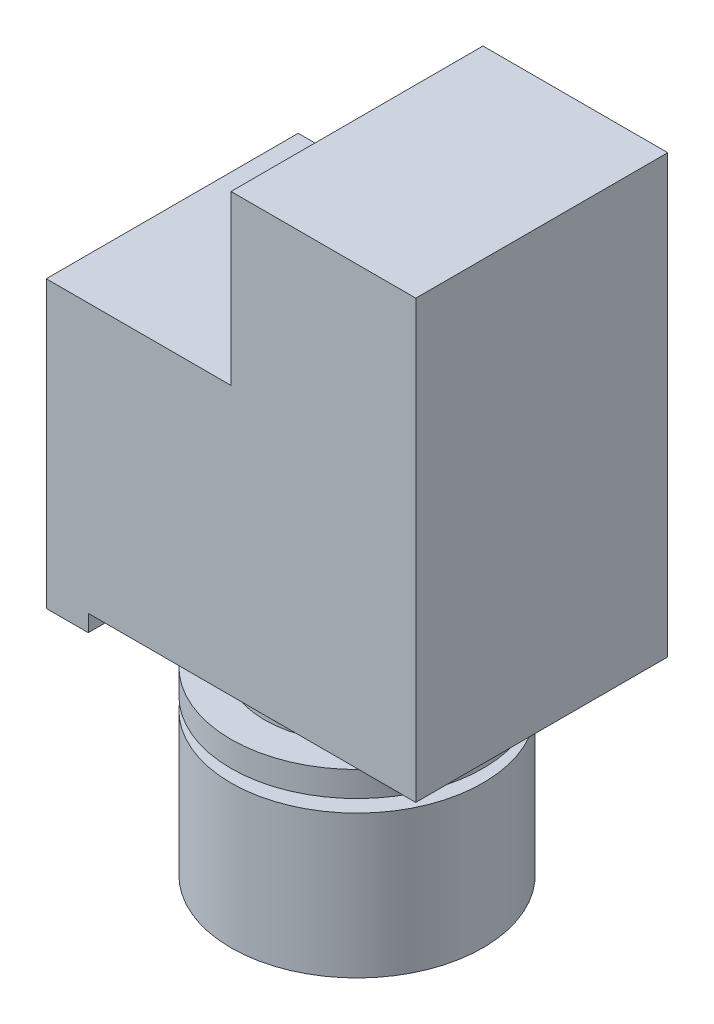
SolidWorks part; units mm, degrees
ref_plane "前基準面" through (0, 0, 0) normal (0, 0, 1) x (1, 0, 0)
ref_plane "上基準面" through (0, 0, 0) normal (0, 1, 0) x (1, 0, 0)
ref_plane "右基準面" through (0, 0, 0) normal (1, 0, 0) x (0, 0, -1)
sketch "草圖1" plane through (0, 0, 0) normal (0, 1, 0) x (1, 0, 0)
  circle A0 centre (0, 0) radius 15
  dimension "D1" = 30
extrude "伸長1" add sketch "草圖1" along normal blind 17
sketch "草圖2" plane through (0, 17, 0) normal (0, 1, 0) x (1, 0, 0)
  circle A0 centre (0, 0) radius 11
  dimension "D1" = 22
extrude "伸長2" add sketch "草圖2" along normal blind 1.5
sketch "草圖3" plane through (0, 18.5, 0) normal (0, 1, 0) x (1, 0, 0)
  circle A0 centre (0, 0) radius 15
  dimension "D1" = 30
extrude "伸長3" add sketch "草圖3" along normal blind 3
sketch "草圖4" plane through (0, 21.5, 0) normal (0, 1, 0) x (1, 0, 0)
  circle A0 centre (0, 0) radius 11
  dimension "D1" = 22
extrude "伸長4" add sketch "草圖4" along normal blind 4.5
cosmetic thread "裝飾螺紋線1" parameters "D2"=20.5
sketch "草圖6" plane through (0, 26, 0) normal (0, 1, 0) x (1, 0, 0)
  line L0 (0, 0) -> (22, 0) construction
  line L1 (-22, 15) -> (22, 15)
  line L2 (-22, 15) -> (-22, -15)
  line L3 (-22, -15) -> (22, -15)
  line L4 (22, 15) -> (22, -15)
  line L5 (0, 0) -> (0, -15) construction
  dimension "D1" = 30
  dimension "D2" = 44
extrude "伸長6" add sketch "草圖6" along normal blind 52
sketch "草圖7" plane through (0, 26, 0) normal (0, -1, 0) x (1, 0, 0)
  line L0 (22, -15) -> (-22, -15) construction
  line L1 (-22, 15) -> (-17, 15)
  line L2 (-22, 15) -> (-22, -15)
  line L3 (-22, -15) -> (-17, -15)
  line L4 (-17, 15) -> (-17, -15)
  dimension "D1" = 5
extrude "伸長7" add sketch "草圖7" along normal blind 2
sketch "草圖8" plane through (0, 0, -15) normal (0, 0, -1) x (-1, 0, 0)
  line L1 (22, 78) -> (0, 78)
  line L2 (22, 78) -> (22, 58)
  line L3 (22, 58) -> (0, 58)
  line L4 (0, 78) -> (0, 58)
  dimension "D1" = 20
extrude "除料-伸長1" cut sketch "草圖8" against normal through all
sketch "草圖9" plane through (0, 0, 0) normal (0, -1, 0) x (1, 0, 0)
  circle A0 centre (0, 0) radius 13
  circle A1 centre (0, 0) radius 12
  dimension "D1" = 24
  dimension "D2" = 26
extrude "除料-伸長2" cut sketch "草圖9" against normal blind 2
